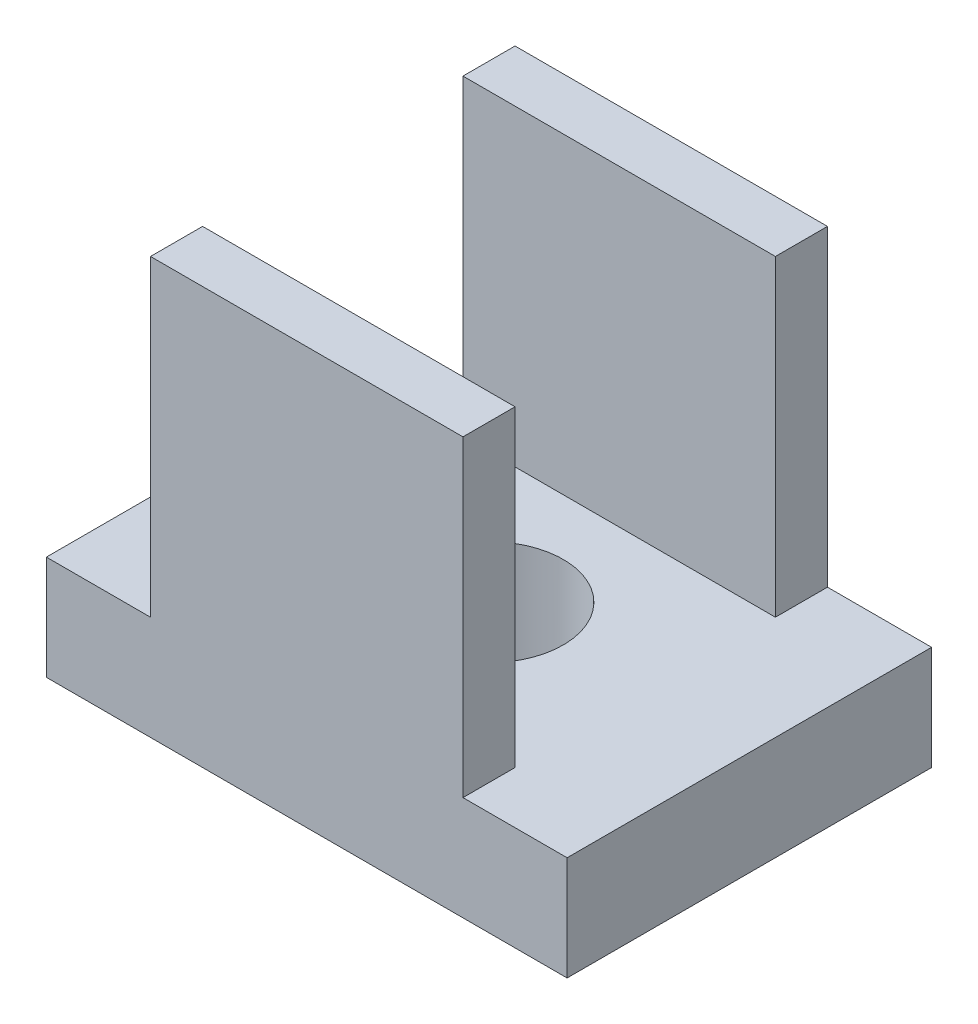
SolidWorks part; units mm, degrees
ref_plane "Front Plane" through (0, 0, 0) normal (0, 0, 1) x (1, 0, 0)
ref_plane "Top Plane" through (0, 0, 0) normal (0, 1, 0) x (1, 0, 0)
ref_plane "Right Plane" through (0, 0, 0) normal (1, 0, 0) x (0, 0, -1)
sketch "Sketch1" plane through (0, 0, 0) normal (0, 1, 0) x (1, 0, 0)
  line L1 (-5, -3.5) -> (5, -3.5)
  line L2 (-5, -3.5) -> (-5, 3.5)
  line L3 (-5, 3.5) -> (5, 3.5)
  line L4 (5, -3.5) -> (5, 3.5)
  line L5 (-5, -3.5) -> (5, 3.5) construction
  line L6 (-5, 3.5) -> (5, -3.5) construction
  point P0 (0, 0)
  dimension "D1" = 10
  dimension "D2" = 7
extrude "Boss-Extrude1" add sketch "Sketch1" along normal blind 2
sketch "Sketch2" plane through (0, 2, 0) normal (0, 1, 0) x (1, 0, 0)
  circle A0 centre (0, 0) radius 1.425
  dimension "D1" = 2.85
extrude "Cut-Extrude2" cut sketch "Sketch2" against normal up to next
sketch "Sketch3" plane through (0, 2, 0) normal (0, 1, 0) x (1, 0, 0)
  line L0 (5, 3.5) -> (-5, 3.5) construction
  line L1 (-3, 3.5) -> (3, 3.5)
  line L2 (-3, 3.5) -> (-3, 2.5)
  line L3 (-3, 2.5) -> (3, 2.5)
  line L4 (3, 3.5) -> (3, 2.5)
  line L5 (-5, -3.5) -> (5, -3.5) construction
  line L6 (-3, -3.5) -> (3, -3.5)
  line L7 (-3, -3.5) -> (-3, -2.5)
  line L8 (-3, -2.5) -> (3, -2.5)
  line L9 (3, -3.5) -> (3, -2.5)
  line L10 (0, 4.9184) -> (0, -5.1981) construction
  dimension "D1" = 1
  dimension "D2" = 6
extrude "Boss-Extrude2" add sketch "Sketch3" along normal blind 6
